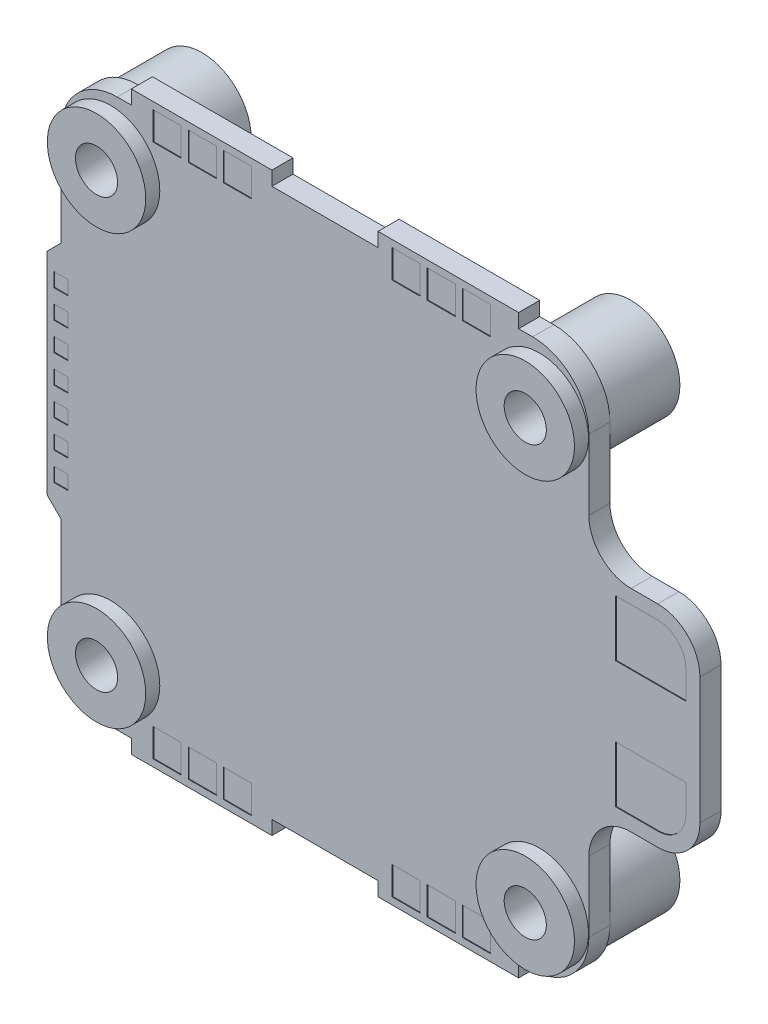
SolidWorks part; units mm, degrees
ref_plane "Alzado" through (0, 0, 0) normal (0, 0, 1) x (1, 0, 0)
ref_plane "Planta" through (0, 0, 0) normal (0, 1, 0) x (1, 0, 0)
ref_plane "Vista lateral" through (0, 0, 0) normal (1, 0, 0) x (0, 0, -1)
sketch "Croquis1" plane through (0, 0, 0) normal (0, 0, 1) x (1, 0, 0)
  line L0 (-19.6668, 13.696) -> (-19.6668, 6.696)
  line L6 (-20.6668, 5.696) -> (-20.6668, -9.304)
  line L8 (-19.6668, -10.304) -> (-19.6668, -17.304)
  line L9 (-20.6668, 5.696) -> (-19.6668, 6.696)
  line L10 (-20.6668, -9.304) -> (-19.6668, -10.304)
  line L11 (-15.6668, 17.696) -> (-14.6668, 17.696)
  line L12 (-14.6668, 17.696) -> (-14.6668, 18.696)
  line L13 (-14.6668, 18.696) -> (-4.6668, 18.696)
  line L14 (-4.6668, 18.696) -> (-4.6668, 17.696)
  line L15 (13.8832, 17.696) -> (12.8832, 17.696)
  line L16 (12.8832, 17.696) -> (12.8832, 18.696)
  line L17 (12.8832, 18.696) -> (2.8832, 18.696)
  line L18 (2.8832, 18.696) -> (2.8832, 17.696)
  line L19 (2.8832, 17.696) -> (-4.6668, 17.696)
  line L20 (-20.6668, -1.804) -> (17.8832, -1.804) construction
  line L21 (2.8832, -21.304) -> (-4.6668, -21.304)
  line L22 (2.8832, -22.304) -> (2.8832, -21.304)
  line L23 (12.8832, -22.304) -> (2.8832, -22.304)
  line L24 (12.8832, -21.304) -> (12.8832, -22.304)
  line L25 (13.8832, -21.304) -> (12.8832, -21.304)
  line L26 (-4.6668, -22.304) -> (-4.6668, -21.304)
  line L27 (-14.6668, -22.304) -> (-4.6668, -22.304)
  line L28 (-14.6668, -21.304) -> (-14.6668, -22.304)
  line L29 (-15.6668, -21.304) -> (-14.6668, -21.304)
  line L30 (17.8832, 13.696) -> (17.8832, 8.696)
  line L31 (20.8832, 5.696) -> (22.7832, 5.696)
  line L32 (25.7832, 2.696) -> (25.7832, -6.304)
  line L33 (22.7832, -9.304) -> (20.8832, -9.304)
  line L34 (17.8832, -12.304) -> (17.8832, -17.304)
  circle A0 centre (-16.1418, 13.446) radius 2.5
  circle A1 centre (14.3582, 13.446) radius 2.5
  circle A2 centre (14.3582, -17.054) radius 2.5
  circle A3 centre (-16.1418, -17.054) radius 2.5
  arc A4 (25.7832, -6.304) -> (22.7832, -9.304) centre (22.7832, -6.304) cw
  arc A5 (22.7832, 5.696) -> (25.7832, 2.696) centre (22.7832, 2.696) cw
  arc A6 (20.8832, -9.304) -> (17.8832, -12.304) centre (20.8832, -12.304) ccw
  arc A7 (17.8832, 8.696) -> (20.8832, 5.696) centre (20.8832, 8.696) ccw
  arc A8 (13.8832, -21.304) -> (17.8832, -17.304) centre (13.8832, -17.304) ccw
  arc A9 (-19.6668, -17.304) -> (-15.6668, -21.304) centre (-15.6668, -17.304) ccw
  arc A10 (13.8832, 17.696) -> (17.8832, 13.696) centre (13.8832, 13.696) cw
  arc A11 (-15.6668, 17.696) -> (-19.6668, 13.696) centre (-15.6668, 13.696) ccw
  point P48 (17.8832, -21.304)
  point P51 (-19.6668, -21.304)
  point P54 (17.8832, 17.696)
  point P57 (-19.6668, 17.696)
  dimension "D3" = 2
  dimension "D10" = 3
  dimension "D11" = 4
  dimension "D1" = 37.55
  dimension "D2" = 39
  dimension "D4" = 2
  dimension "D5" = 4.25
  dimension "D6" = 3.525
  dimension "D7" = 46.45
  dimension "D8" = 12
  dimension "D9" = 12
extrude "Saliente-Extruir1" add sketch "Croquis1" along normal blind 1.5
sketch "Croquis2" plane through (0, 0, 1.5) normal (0, 0, 1) x (1, 0, 0)
  line L0 (-18.6418, -17.054) -> (-13.6418, -17.054)
  circle A0 centre (-16.1418, -17.054) radius 2.5 construction
ref_plane "Plano1" through (0, -17.054, 0) normal (0, -1, 0) x (-1, 0, 0)
sketch "Croquis3" plane through (0, -17.054, 0) normal (0, -1, 0) x (-1, 0, 0)
  line L0 (18.6418, -1.5) -> (19.6418, -1.5)
  line L1 (19.6418, -1.5) -> (19.6418, -2.5)
  line L2 (18.6418, -1.5) -> (13.6418, -1.5) construction
  line L3 (16.1418, -1.5) -> (16.1418, -2.5) construction
  line L5 (16.1418, -2.5) -> (16.1418, 1) construction
  line L7 (19.6418, 5) -> (19.6418, 0)
  line L8 (19.6418, 0) -> (18.6418, 0)
  line L9 (18.6418, 0) -> (18.6418, -1.5)
  line L10 (19.6418, -2.5) -> (17.6418, -2.5)
  line L11 (17.6418, -2.5) -> (17.6418, 5)
  line L12 (17.6418, 5) -> (19.6418, 5)
  dimension "D1" = 5
  dimension "D2" = 1
  dimension "D3" = 1
  dimension "D4" = 1
  dimension "D6" = 2
revolve "Revolución1" add sketch "Croquis3" angle 360 about L5
pattern_linear "MatrizL1" count 2 spacing 30.5 along (1, 0, 0) count 2 spacing 30.5 along (0, 1, 0) of "Revolución1"
sketch "Croquis4" plane through (0, 0, 1.5) normal (0, 0, 1) x (1, 0, 0)
  line L0 (20.8832, -9.304) -> (22.7832, -9.304) construction
  line L1 (19.7832, -8.304) -> (22.7832, -8.304)
  line L2 (19.7832, -8.304) -> (19.7832, -4.304)
  line L3 (19.7832, -4.304) -> (24.7832, -4.304)
  line L4 (24.7832, -6.304) -> (24.7832, -4.304)
  line L9 (8.8832, -21.804) -> (10.8832, -21.804)
  line L10 (8.8832, -21.804) -> (8.8832, -19.804)
  line L11 (8.8832, -19.804) -> (10.8832, -19.804)
  line L12 (10.8832, -21.804) -> (10.8832, -19.804)
  line L13 (-20.1668, -8.304) -> (-19.1668, -8.304)
  line L14 (-20.1668, -8.304) -> (-20.1668, -7.304)
  line L15 (-20.1668, -7.304) -> (-19.1668, -7.304)
  line L16 (-19.1668, -8.304) -> (-19.1668, -7.304)
  line L17 (25.7832, -6.304) -> (25.7832, 2.696) construction
  line L18 (25.7832, -1.804) -> (-20.6668, -1.804) construction
  line L19 (-20.6668, 5.696) -> (-20.6668, -9.304) construction
  line L20 (12.8832, -22.304) -> (12.8832, -21.304) construction
  line L21 (2.8832, -22.304) -> (12.8832, -22.304) construction
  line L22 (6.3832, -21.804) -> (8.3832, -21.804)
  line L23 (6.3832, -21.804) -> (6.3832, -19.804)
  line L24 (6.3832, -19.804) -> (8.3832, -19.804)
  line L25 (8.3832, -21.804) -> (8.3832, -19.804)
  line L26 (3.8832, -21.804) -> (5.8832, -21.804)
  line L27 (3.8832, -21.804) -> (3.8832, -19.804)
  line L28 (3.8832, -19.804) -> (5.8832, -19.804)
  line L29 (5.8832, -21.804) -> (5.8832, -19.804)
  line L30 (-8.1168, -21.804) -> (-6.1168, -21.804)
  line L31 (-8.1168, -21.804) -> (-8.1168, -19.804)
  line L32 (-8.1168, -19.804) -> (-6.1168, -19.804)
  line L33 (-6.1168, -21.804) -> (-6.1168, -19.804)
  line L34 (-10.6168, -21.804) -> (-8.6168, -21.804)
  line L35 (-10.6168, -21.804) -> (-10.6168, -19.804)
  line L36 (-10.6168, -19.804) -> (-8.6168, -19.804)
  line L37 (-8.6168, -21.804) -> (-8.6168, -19.804)
  line L38 (-13.1168, -21.804) -> (-11.1168, -21.804)
  line L39 (-13.1168, -21.804) -> (-13.1168, -19.804)
  line L40 (-13.1168, -19.804) -> (-11.1168, -19.804)
  line L41 (-11.1168, -21.804) -> (-11.1168, -19.804)
  line L42 (-20.1668, -6.304) -> (-19.1668, -6.304)
  line L43 (-20.1668, -6.304) -> (-20.1668, -5.304)
  line L44 (-20.1668, -5.304) -> (-19.1668, -5.304)
  line L45 (-19.1668, -6.304) -> (-19.1668, -5.304)
  line L46 (-20.1668, -4.304) -> (-19.1668, -4.304)
  line L47 (-20.1668, -4.304) -> (-20.1668, -3.304)
  line L48 (-20.1668, -3.304) -> (-19.1668, -3.304)
  line L49 (-19.1668, -4.304) -> (-19.1668, -3.304)
  line L50 (-20.1668, -2.304) -> (-19.1668, -2.304)
  line L51 (-20.1668, -2.304) -> (-20.1668, -1.304)
  line L52 (-20.1668, -1.304) -> (-19.1668, -1.304)
  line L53 (-19.1668, -2.304) -> (-19.1668, -1.304)
  line L54 (-20.1668, -0.304) -> (-19.1668, -0.304)
  line L55 (-20.1668, -0.304) -> (-20.1668, 0.696)
  line L56 (-20.1668, 0.696) -> (-19.1668, 0.696)
  line L57 (-19.1668, -0.304) -> (-19.1668, 0.696)
  line L58 (-20.1668, 1.696) -> (-19.1668, 1.696)
  line L59 (-20.1668, 1.696) -> (-20.1668, 2.696)
  line L60 (-20.1668, 2.696) -> (-19.1668, 2.696)
  line L61 (-19.1668, 1.696) -> (-19.1668, 2.696)
  line L62 (-20.1668, 3.696) -> (-19.1668, 3.696)
  line L63 (-20.1668, 3.696) -> (-20.1668, 4.696)
  line L64 (-20.1668, 4.696) -> (-19.1668, 4.696)
  line L65 (-19.1668, 3.696) -> (-19.1668, 4.696)
  line L66 (-11.1168, 18.196) -> (-11.1168, 16.196)
  line L67 (-13.1168, 16.196) -> (-11.1168, 16.196)
  line L68 (-13.1168, 18.196) -> (-13.1168, 16.196)
  line L69 (-13.1168, 18.196) -> (-11.1168, 18.196)
  line L70 (-8.6168, 18.196) -> (-8.6168, 16.196)
  line L71 (-10.6168, 16.196) -> (-8.6168, 16.196)
  line L72 (-10.6168, 18.196) -> (-10.6168, 16.196)
  line L73 (-10.6168, 18.196) -> (-8.6168, 18.196)
  line L74 (-6.1168, 18.196) -> (-6.1168, 16.196)
  line L75 (-8.1168, 16.196) -> (-6.1168, 16.196)
  line L76 (-8.1168, 18.196) -> (-8.1168, 16.196)
  line L77 (-8.1168, 18.196) -> (-6.1168, 18.196)
  line L78 (5.8832, 18.196) -> (5.8832, 16.196)
  line L79 (3.8832, 16.196) -> (5.8832, 16.196)
  line L80 (3.8832, 18.196) -> (3.8832, 16.196)
  line L81 (3.8832, 18.196) -> (5.8832, 18.196)
  line L82 (8.3832, 18.196) -> (8.3832, 16.196)
  line L83 (6.3832, 16.196) -> (8.3832, 16.196)
  line L84 (6.3832, 18.196) -> (6.3832, 16.196)
  line L85 (6.3832, 18.196) -> (8.3832, 18.196)
  line L86 (10.8832, 18.196) -> (10.8832, 16.196)
  line L87 (8.8832, 16.196) -> (10.8832, 16.196)
  line L88 (8.8832, 18.196) -> (8.8832, 16.196)
  line L89 (8.8832, 18.196) -> (10.8832, 18.196)
  line L90 (24.7832, 2.696) -> (24.7832, 0.696)
  line L91 (19.7832, 0.696) -> (24.7832, 0.696)
  line L92 (19.7832, 4.696) -> (19.7832, 0.696)
  line L93 (19.7832, 4.696) -> (22.7832, 4.696)
  arc A0 (22.7832, -8.304) -> (24.7832, -6.304) centre (22.7832, -6.304) ccw
  arc A1 (22.7832, 4.696) -> (24.7832, 2.696) centre (22.7832, 2.696) cw
  point P18 (21.8332, -9.304)
  dimension "D1" = 2
  dimension "D2" = 2
  dimension "D3" = 4
  dimension "D4" = 5
  dimension "D5" = 1
  dimension "D6" = 1
  dimension "D7" = 2
  dimension "D8" = 2
  dimension "D9" = 0.5
  dimension "D12" = 0.5
  dimension "D13" = 1
  dimension "D14" = 1
  dimension "D15" = 7
  dimension "D16" = 2
  dimension "D10" = 3
  dimension "D11" = 2
extrude "Cortar-Extruir1" cut sketch "Croquis4" against normal blind 0.05
